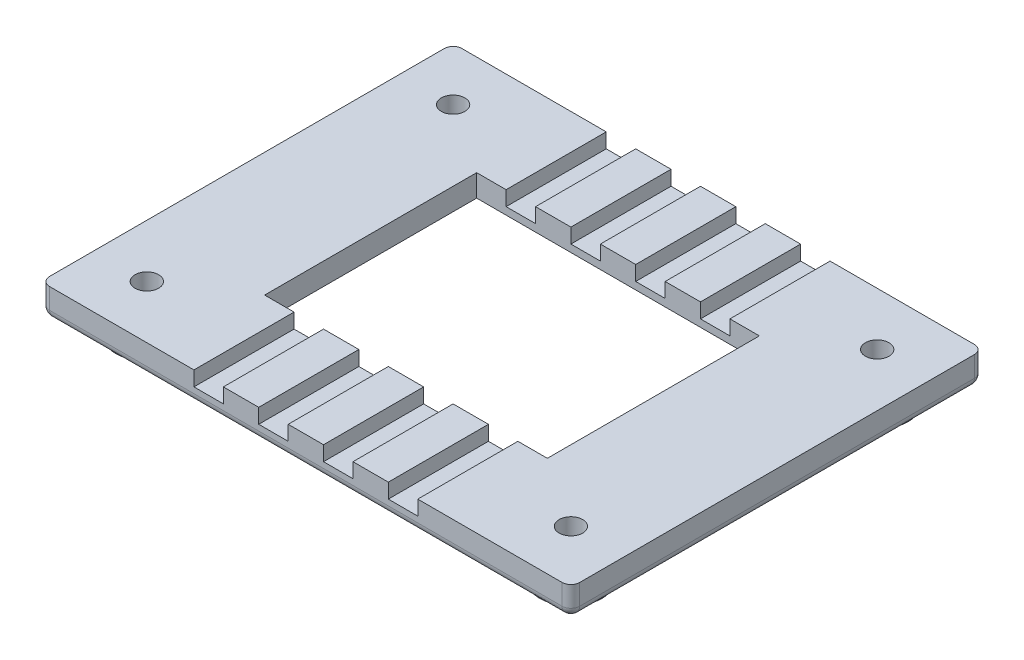
SolidWorks part; units mm, degrees
ref_plane "Front Plane" through (0, 0, 0) normal (0, 0, 1) x (1, 0, 0)
ref_plane "Top Plane" through (0, 0, 0) normal (0, 1, 0) x (1, 0, 0)
ref_plane "Right Plane" through (0, 0, 0) normal (1, 0, 0) x (0, 0, -1)
sketch "Sketch1" plane through (0, 0, 0) normal (0, 1, 0) x (1, 0, 0)
  line L1 (45, -35) -> (-45, -35)
  line L2 (45, -35) -> (45, 35)
  line L3 (45, 35) -> (-45, 35)
  line L4 (-45, -35) -> (-45, 35)
  line L5 (45, -35) -> (-45, 35) construction
  line L6 (45, 35) -> (-45, -35) construction
  point P0 (0, 0)
  dimension "D1" = 70
  dimension "D2" = 90
extrude "Base Plate" add sketch "Sketch1" along normal blind 5
sketch "Sketch7" plane through (0, 5, 0) normal (0, 1, 0) x (1, 0, 0)
  line L2 (0, 0) -> (-11.5051, 0) construction
  line L3 (-45, 35) -> (-45, -35) construction
  line L4 (0, 13.9859) -> (0, 0) construction
  line L5 (45, 35) -> (-45, 35) construction
  circle A0 centre (-36, 26) radius 2
  circle A1 centre (-36, -26) radius 2
  circle A2 centre (36, -26) radius 2
  circle A3 centre (36, 26) radius 2
  dimension "D1" = 4
  dimension "D2" = 9
  dimension "D3" = 9
extrude "Screw Cut" cut sketch "Sketch7" against normal blind 5
sketch "Sketch13" plane through (0, 5, 0) normal (0, 1, 0) x (1, 0, 0)
  line L1 (-24, 18) -> (24, 18)
  line L2 (-24, 18) -> (-24, -18)
  line L3 (-24, -18) -> (24, -18)
  line L4 (24, 18) -> (24, -18)
  line L5 (-24, 18) -> (24, -18) construction
  line L6 (-24, -18) -> (24, 18) construction
  point P0 (0, 0)
  dimension "D1" = 48
  dimension "D2" = 36
extrude "Screen Cut Out" cut sketch "Sketch13" against normal blind 10
sketch "Sketch21" plane through (0, 0, 0) normal (0, -1, 0) x (1, 0, 0)
  line L0 (-24, 18) -> (24, 18) construction
  line L1 (-24, 18) -> (24, 18)
  line L2 (24, 18) -> (24, -18) construction
  line L3 (-26, 20) -> (26, 20)
  line L6 (26, 20) -> (26, -20)
  line L8 (24, 18) -> (24, -18)
  line L9 (26, -20) -> (-26, -20)
  line L11 (24, -18) -> (-24, -18)
  line L14 (-24, -18) -> (-24, 18)
  line L16 (-26, -20) -> (-26, 20)
  dimension "D1" = 2
  dimension "D2" = 2
  dimension "D3" = 2
  dimension "D4" = 2
extrude "Screen Mount" cut sketch "Sketch21" against normal blind 1.25
sketch "Sketch15" plane through (-42.5, 0, -25) normal (0, -1, 0) x (1, 0, 0)
  line L0 (42.5, -10) -> (42.5, 60) construction
  line L1 (87.5, -10) -> (-2.5, -10) construction
  line L2 (-2.5, -10) -> (-2.5, 60) construction
  line L3 (-2.5, 25) -> (42.5, 25) construction
  circle A0 centre (6.5, -1) radius 5.25
  circle A1 centre (6.5, 51) radius 5.25
  circle A2 centre (78.5, 51) radius 5.25
  circle A3 centre (78.5, -1) radius 5.25
  dimension "D1" = 10.5
extrude "M3 Nut Outer" add sketch "Sketch15" along normal blind 3
sketch "Sketch18" plane through (0, 0, 0) normal (0, 1, 0) x (1, 0, 0)
  line L0 (0, 0) -> (0, -29.8583) construction
  line L2 (-49.7998, 0) -> (0, 0) construction
  circle A0 centre (-36, 26) radius 2
  circle A1 centre (-36, 26) radius 2 construction
  circle A2 centre (-36, -26) radius 2
  circle A3 centre (36, 26) radius 2
  circle A4 centre (36, -26) radius 2
extrude "Screw Hole" cut sketch "Sketch18" against normal up to surface (3 mm away) up to face at (-36, -3, -31.25)
sketch "Sketch19" plane through (0, -3, 0) normal (0, -1, 0) x (1, 0, 0)
  line L0 (0, 0) -> (0, -22.785) construction
  line L1 (-36, -22.7091) -> (-38.85, -24.3546)
  line L2 (-38.85, -24.3546) -> (-38.85, -27.6454)
  line L3 (-38.85, -27.6454) -> (-36, -29.2909)
  line L4 (-36, -29.2909) -> (-33.15, -27.6454)
  line L5 (-33.15, -27.6454) -> (-33.15, -24.3546)
  line L6 (-33.15, -24.3546) -> (-36, -22.7091)
  line L7 (-33.15, 24.3546) -> (-36, 22.7091)
  line L8 (-38.1664, 0) -> (0, 0) construction
  line L9 (-33.15, 27.6454) -> (-33.15, 24.3546)
  line L10 (-36, 29.2909) -> (-33.15, 27.6454)
  line L11 (-38.85, 27.6454) -> (-36, 29.2909)
  line L12 (-38.85, 24.3546) -> (-38.85, 27.6454)
  line L13 (-36, 22.7091) -> (-38.85, 24.3546)
  line L14 (33.15, -24.3546) -> (36, -22.7091)
  line L15 (33.15, -27.6454) -> (33.15, -24.3546)
  line L16 (36, -29.2909) -> (33.15, -27.6454)
  line L17 (38.85, -27.6454) -> (36, -29.2909)
  line L18 (38.85, -24.3546) -> (38.85, -27.6454)
  line L19 (36, -22.7091) -> (38.85, -24.3546)
  line L20 (36, 22.7091) -> (38.85, 24.3546)
  line L21 (38.85, 24.3546) -> (38.85, 27.6454)
  line L22 (38.85, 27.6454) -> (36, 29.2909)
  line L23 (36, 29.2909) -> (33.15, 27.6454)
  line L24 (33.15, 27.6454) -> (33.15, 24.3546)
  line L25 (33.15, 24.3546) -> (36, 22.7091)
  circle A2 centre (-36, -26) radius 2.85 construction
  circle A3 centre (-36, 26) radius 2.85 construction
  circle A4 centre (36, -26) radius 2.85 construction
  circle A5 centre (36, 26) radius 2.85 construction
  dimension "D1" = 5.7
extrude "M3 Nut" cut sketch "Sketch19" against normal blind 3
sketch "Sketch20" plane through (0, 0, -35) normal (0, 0, -1) x (-1, 0, 0)
  line L0 (-45, 5) -> (45, 5) construction
  line L1 (-11, 5) -> (-11, 1.5238) construction
  line L2 (-3, 5) -> (-8, 5)
  line L3 (-3, 5) -> (-3, 2.5)
  line L4 (-3, 2.5) -> (-8, 2.5)
  line L5 (-8, 5) -> (-8, 2.5)
  line L6 (-19, 5) -> (-14, 5)
  line L7 (0, 5) -> (0, 3.5097) construction
  line L8 (-20.75, 1.5238) -> (-20.75, 5) construction
  line L9 (-14, 5) -> (-14, 2.5)
  line L10 (-19, 2.5) -> (-14, 2.5)
  line L11 (-19, 5) -> (-19, 2.5)
  line L29 (19, 5) -> (19, 2.5)
  line L30 (19, 5) -> (14, 5)
  line L31 (19, 2.5) -> (14, 2.5)
  line L32 (14, 5) -> (14, 2.5)
  line L33 (3, 5) -> (8, 5)
  line L34 (8, 5) -> (8, 2.5)
  line L35 (3, 2.5) -> (8, 2.5)
  line L36 (3, 5) -> (3, 2.5)
  dimension "D1" = 2.5
  dimension "D2" = 5
  dimension "D3" = 3
  dimension "D4" = 3
  dimension "D5" = 1.75
extrude "Water Groves" cut sketch "Sketch20" against normal up to surface (70 mm away) up to face at (0, 2.5, 35)
fillet "Fillet1" radius 1.5 1 edges at (0, 0, -35)
fillet "Fillet2" radius 1.5 3 edges at (-45, 0, 0.75) (-45, 0.4393, -34.5607) (-45, 3.25, -35)
fillet "Fillet3" radius 1.5 3 edges at (0.75, 0, 35) (-44.5607, 0.4393, 35) (-45, 3.25, 35)
fillet "Fillet4" radius 1.5 5 edges at (45, 0.4393, -34.5607) (45, 0, 0) (45, 0.4393, 34.5607) (45, 3.25, -35) (45, 3.25, 35)
